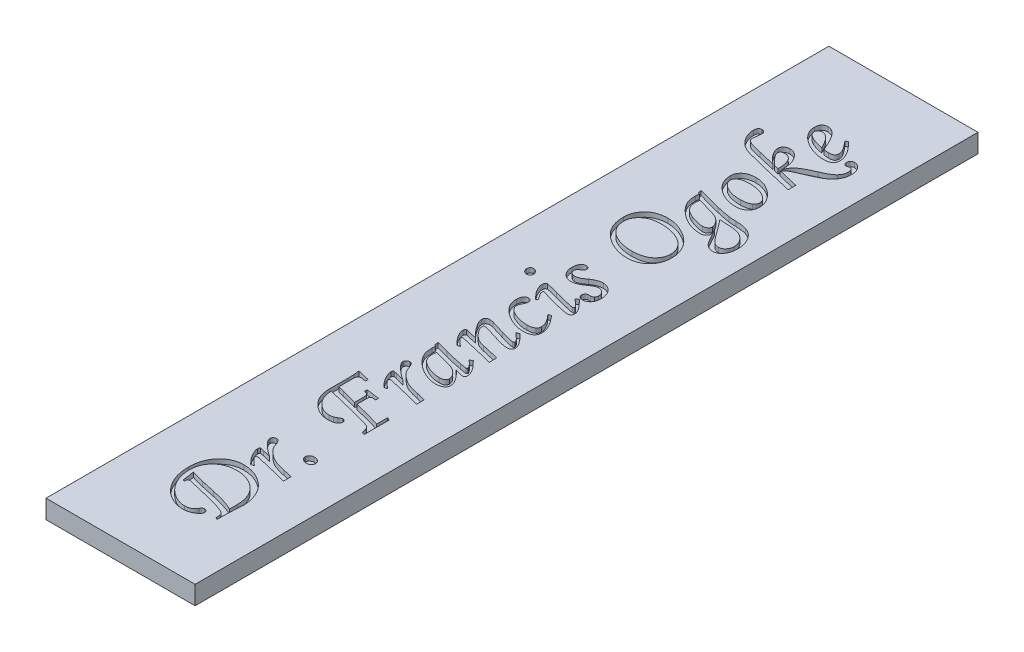
SolidWorks part; units mm, degrees
ref_plane "Front Plane" through (0, 0, 0) normal (0, 0, 1) x (1, 0, 0)
ref_plane "Top Plane" through (0, 0, 0) normal (0, 1, 0) x (1, 0, 0)
ref_plane "Right Plane" through (0, 0, 0) normal (1, 0, 0) x (0, 0, -1)
sketch "Sketch1" plane through (0, 0, 0) normal (0, 0, 1) x (1, 0, 0)
  line L0 (0, 1.5875) -> (0, -1.5875)
  line L1 (-12.7, 0) -> (12.7, 0) construction
  point P6 (0, 0)
  dimension "Width" = 25.4
  dimension "Thk" = 3.175
sketch "Sketch2" plane through (0, 0, 0) normal (1, 0, 0) x (0, 0, -1)
  line L0 (66.675, 0) -> (-66.675, 0)
  point P4 (0, 0)
  dimension "Length" = 133.35
sketch "Sketch3" plane through (0, 0, 0) normal (0, 0, 1) x (1, 0, 0)
  line L1 (12.7, 1.5875) -> (-12.7, 1.5875)
  line L2 (12.7, 1.5875) -> (12.7, -1.5875)
  line L3 (12.7, -1.5875) -> (-12.7, -1.5875)
  line L4 (-12.7, 1.5875) -> (-12.7, -1.5875)
  line L5 (12.7, 1.5875) -> (-12.7, -1.5875) construction
  line L6 (12.7, -1.5875) -> (-12.7, 1.5875) construction
  point P0 (0, 0)
extrude "Boss-Extrude1" add sketch "Sketch3" along normal up to vertex (66.675 mm away) and the other way up to vertex (66.675 mm away) up to point (0, 0, 66.675) other way up to point (0, 0, -66.675)
sketch "Sketch4" plane through (0, 1.5875, 0) normal (0, 1, 0) x (1, 0, 0)
  line L0 (0, 0) -> (5, 0) construction
  line L1 (5, -66.675) -> (5, 66.675) construction
  line L2 (12.7, 66.675) -> (-12.7, 66.675) construction
  text T0 "Dr. Francis Ogoke " font "Monotype Corsiva" height 10
  point P8 (5, 0)
  dimension "D1" = 5
extrude "Cut-Extrude1" cut sketch "Sketch4" against normal blind 0.7937
